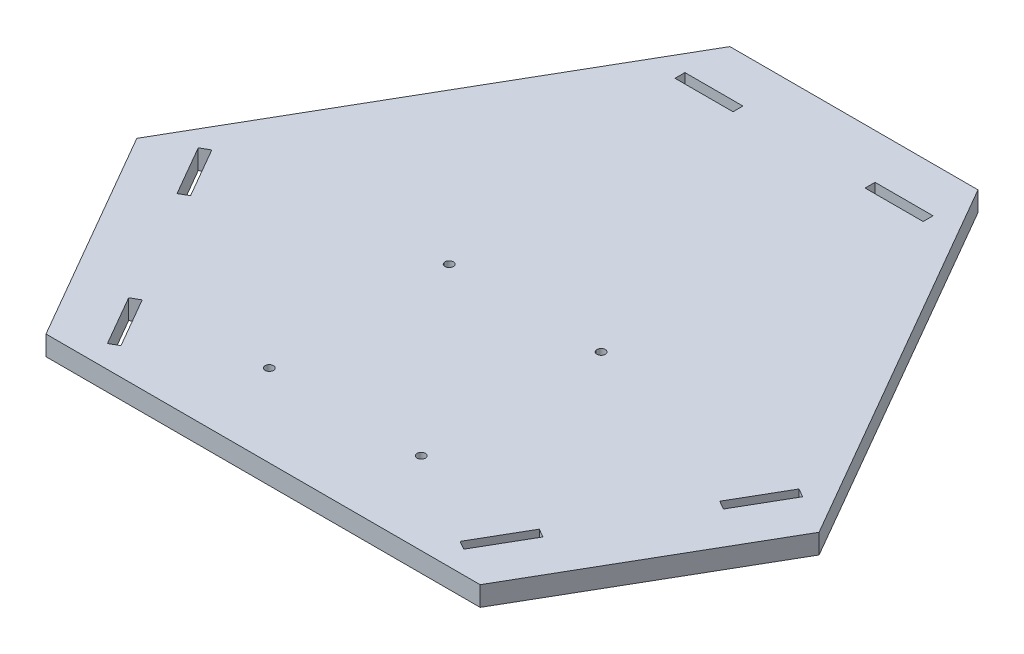
SolidWorks part; units mm, degrees
ref_plane "Front Plane" through (0, 0, 0) normal (0, 0, 1) x (1, 0, 0)
ref_plane "Top Plane" through (0, 0, 0) normal (0, 1, 0) x (1, 0, 0)
ref_plane "Right Plane" through (0, 0, 0) normal (1, 0, 0) x (0, 0, -1)
sketch "Sketch1" plane through (0, 0, 0) normal (0, 1, 0) x (1, 0, 0)
  line L0 (70, -86.6025) -> (110, -17.3205)
  line L1 (110, -17.3205) -> (40, 103.923)
  line L2 (-40, 103.923) -> (-110, -17.3205)
  line L3 (-70, -86.6025) -> (70, -86.6025)
  line L4 (-110, -17.3205) -> (-70, -86.6025)
  line L5 (-40, 103.923) -> (40, 103.923)
  line L6 (0, 103.923) -> (0, -86.6025) construction
  line L7 (90, -51.9615) -> (-75, 43.3013) construction
  line L8 (-110, -17.3205) -> (-88.4498, -4.8785) construction
  line L9 (-90, -51.9615) -> (0, 0) construction
  line L10 (-100.65, -33.5152) -> (-79.0998, -21.0731) construction
  line L11 (-94.6714, -8.4705) -> (-85.3214, -24.6652)
  line L12 (-85.3214, -24.6652) -> (-88.0926, -26.2652)
  line L13 (-88.0926, -26.2652) -> (-97.4426, -10.0705)
  line L14 (-97.4426, -10.0705) -> (-94.6714, -8.4705)
  line L16 (-57.4426, -79.3525) -> (-54.6714, -77.7525)
  line L17 (-66.7926, -63.1579) -> (-57.4426, -79.3525)
  line L18 (-64.0214, -61.5579) -> (-66.7926, -63.1579)
  line L19 (-54.6714, -77.7525) -> (-64.0214, -61.5579)
  line L20 (54.6714, -77.7525) -> (64.0214, -61.5579)
  line L21 (64.0214, -61.5579) -> (66.7926, -63.1579)
  line L22 (66.7926, -63.1579) -> (57.4426, -79.3525)
  line L23 (57.4426, -79.3525) -> (54.6714, -77.7525)
  line L24 (97.4426, -10.0705) -> (94.6714, -8.4705)
  line L25 (88.0926, -26.2652) -> (97.4426, -10.0705)
  line L26 (85.3214, -24.6652) -> (88.0926, -26.2652)
  line L27 (94.6714, -8.4705) -> (85.3214, -24.6652)
  line L28 (40, 86.223) -> (21.3, 86.223)
  line L29 (21.3, 86.223) -> (21.3, 89.423)
  line L30 (21.3, 89.423) -> (40, 89.423)
  line L31 (40, 89.423) -> (40, 86.223)
  line L32 (-40, 89.423) -> (-40, 86.223)
  line L33 (-21.3, 89.423) -> (-40, 89.423)
  line L34 (-21.3, 86.223) -> (-21.3, 89.423)
  line L35 (-40, 86.223) -> (-21.3, 86.223)
  circle A0 centre (0, 0) radius 86.6025 construction
  point P13 (-105.325, -25.4178)
  point P35 (105.325, -25.4178)
  dimension "D1" = 140
  dimension "D2" = 80
  dimension "D3" = 9.35
  dimension "D4" = 18.7
  dimension "D5" = 9.35
  dimension "D6" = 3.2
  dimension "D7" = 14.5
extrude "Boss-Extrude1" add sketch "Sketch1" along normal blind 6.35
sketch "Sketch2" plane through (0, 6.35, 0) normal (0, 1, 0) x (1, 0, 0)
  line L1 (-24.5, -60.1025) -> (24.5, -60.1025) construction
  line L2 (-24.5, -60.1025) -> (-24.5, -2.1025) construction
  line L3 (-24.5, -2.1025) -> (24.5, -2.1025) construction
  line L4 (24.5, -60.1025) -> (24.5, -2.1025) construction
  line L5 (-24.5, -60.1025) -> (24.5, -2.1025) construction
  line L6 (-24.5, -2.1025) -> (24.5, -60.1025) construction
  line L7 (-70, -86.6025) -> (70, -86.6025) construction
  circle A0 centre (-24.5, -60.1025) radius 1.35
  circle A1 centre (24.5, -60.1025) radius 1.35
  circle A2 centre (24.5, -2.1025) radius 1.35
  circle A3 centre (-24.5, -2.1025) radius 1.35
  point P0 (0, -31.1025)
  point P9 (0, -2.1025)
  dimension "D2" = 2.7
  dimension "D1" = 58
  dimension "D3" = 49
  dimension "D4" = 26.5
  dimension "D5" = 0
extrude "Cut-Extrude1" cut sketch "Sketch2" against normal up to surface (6.35 mm away) up to face at (30.65, 0, -87.823)
equation "\"D5@Sketch1\"=\"D4@Sketch1\"/2"
equation "\"D3@Sketch1\"=\"D5@Sketch1\""
